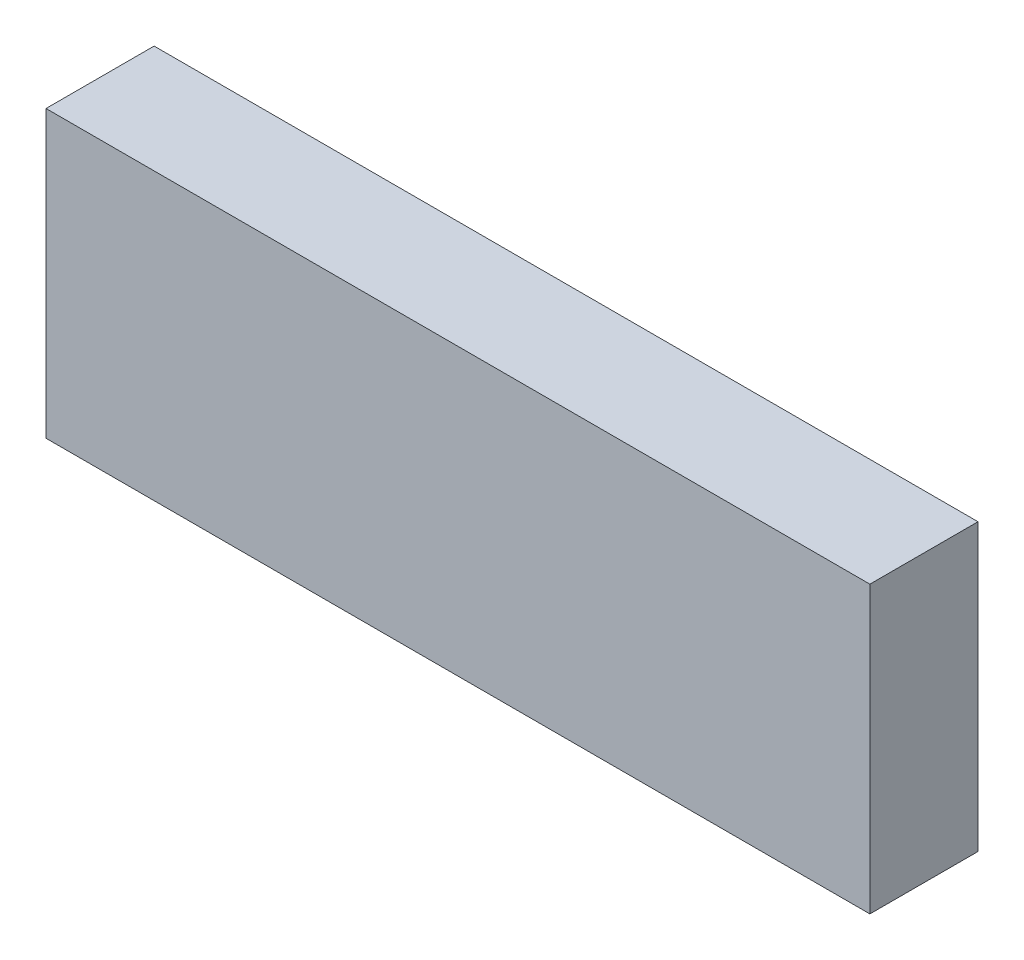
SolidWorks part; units mm, degrees
ref_plane "Front Plane" through (0, 0, 0) normal (0, 0, 1) x (1, 0, 0)
ref_plane "Top Plane" through (0, 0, 0) normal (0, 1, 0) x (1, 0, 0)
ref_plane "Right Plane" through (0, 0, 0) normal (1, 0, 0) x (0, 0, -1)
sketch "Sketch1" plane through (0, 0, 0) normal (0, 0, 1) x (1, 0, 0)
  line L0 (-1.27, 1.3716) -> (6.35, 1.3716)
  line L1 (6.35, 1.3716) -> (6.35, -1.27)
  line L2 (6.35, -1.27) -> (-1.27, -1.27)
  line L3 (-1.27, -1.27) -> (-1.27, 1.3716)
extrude "Component_Outline" add sketch "Sketch1" along normal blind 1 separate body
sketch3d "3DSketch1"
  line L0 (0, 0, 0) -> (1, 0, 0)
  line L1 (0, 0, 0) -> (0, 1, 0)
  line L2 (0, 0, 0) -> (0, 0, 1)
  point P0 (0, 0, 0)
